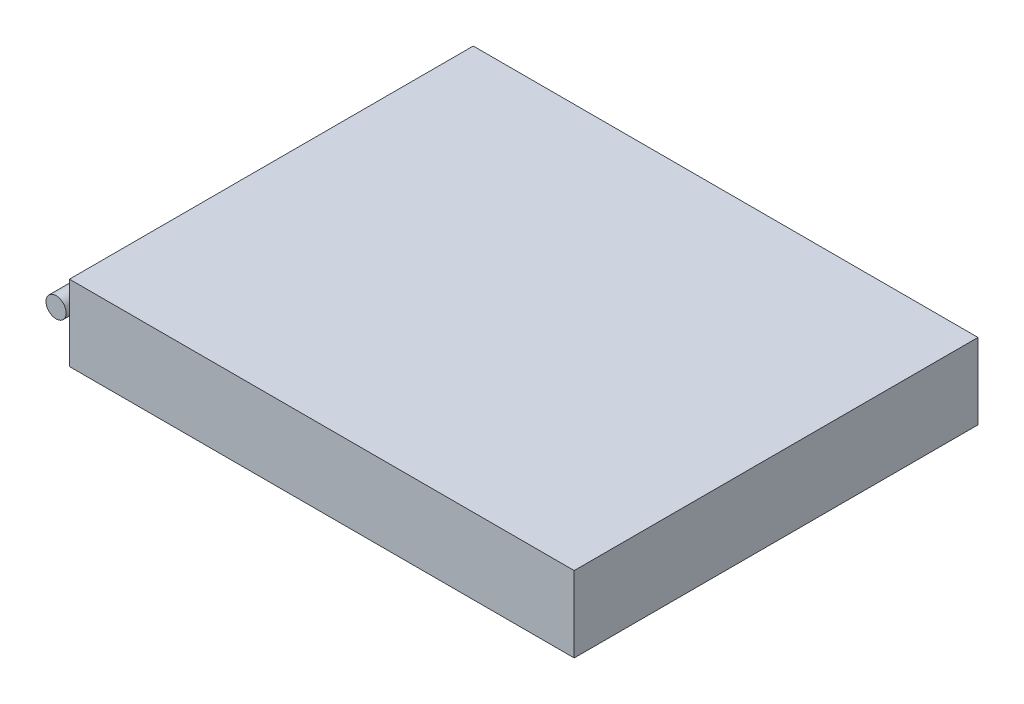
SolidWorks part; units mm, degrees
ref_plane "Front" through (0, 0, 0) normal (0, 0, 1) x (1, 0, 0)
ref_plane "Top" through (0, 0, 0) normal (0, 1, 0) x (1, 0, 0)
ref_plane "Right" through (0, 0, 0) normal (1, 0, 0) x (0, 0, -1)
sketch "Sketch1" plane through (0, 0, 0) normal (0, 1, 0) x (1, 0, 0)
  line L1 (0, 0) -> (50, 0)
  line L2 (0, 0) -> (0, 40)
  line L3 (0, 40) -> (50, 40)
  line L4 (50, 0) -> (50, 40)
  dimension "D1" = 50
  dimension "D2" = 40
extrude "Boss-Extrude1" add sketch "Sketch1" along normal blind 7.5
sketch "Sketch2" plane through (0, 0, 0) normal (-1, 0, 0) x (0, 0, 1)
  line L0 (-40, 7.5) -> (0, 7.5) construction
  line L1 (-40, 7.5) -> (-40, 0) construction
  circle A0 centre (-35, 3.75) radius 1
  point P4 (-40, 3.75)
  dimension "D2" = 2
  dimension "D1" = 3.75
  dimension "D3" = 5
ref_plane "Plane1" through (0, 3.75, 0) normal (0, 1, 0) x (1, 0, 0)
sketch "Sketch3" plane through (0, 3.75, 0) normal (0, 1, 0) x (1, 0, 0)
  line L0 (0, 35) -> (-0.5, 35)
  line L1 (0, 36) -> (0, 34) construction
  line L2 (-2, 33.5) -> (-2, 10)
  line L3 (0, 40) -> (0, 0) construction
  arc A0 (-2, 33.5) -> (-0.5, 35) centre (-0.5, 33.5) cw
  point P9 (-2, 35)
  dimension "D3" = 1.5
  dimension "D1" = 2
  dimension "D2" = 25
sweep "Sweep1" add profiles "Sketch2" path "Sketch3"
sketch "Sketch4" plane through (0, 0, 0) normal (-1, 0, 0) x (0, 0, 1)
  line L0 (50, 3.75) -> (-50, 3.75) construction
  line L1 (0, 7.5) -> (0, 0) construction
  circle A0 centre (-5, 3.75) radius 1
  dimension "D1" = 2
  dimension "D2" = 5
sketch "Sketch5" plane through (0, 3.75, 0) normal (0, 1, 0) x (1, 0, 0)
  line L0 (0, 5) -> (-0.5, 5)
  line L1 (0, 6) -> (0, 4) construction
  line L2 (-2, 3.5) -> (-2, 0.6745)
  line L3 (0, 40) -> (0, 0) construction
  arc A0 (-2, 3.5) -> (-0.5, 5) centre (-0.5, 3.5) cw
  dimension "D2" = 1.5
  dimension "D1" = 2
sweep "Sweep2" add profiles "Sketch4" path "Sketch5"
sketch "Sketch6" plane through (0, 7.5, 0) normal (0, 1, 0) x (1, 0, 0)
  line L0 (25, 40) -> (25, 0) construction
  line L1 (50, 40) -> (0, 40) construction
  line L2 (0, 0) -> (50, 0) construction
  line L3 (0, 20) -> (50, 20) construction
  line L4 (0, 40) -> (0, 0) construction
  line L5 (50, 0) -> (50, 40) construction
ref_plane "CL Y" through (25, 0, 0) normal (1, 0, 0) x (0, 0, -1)
ref_plane "CL X" through (0, 0, -20) normal (0, 0, 1) x (1, 0, 0)
